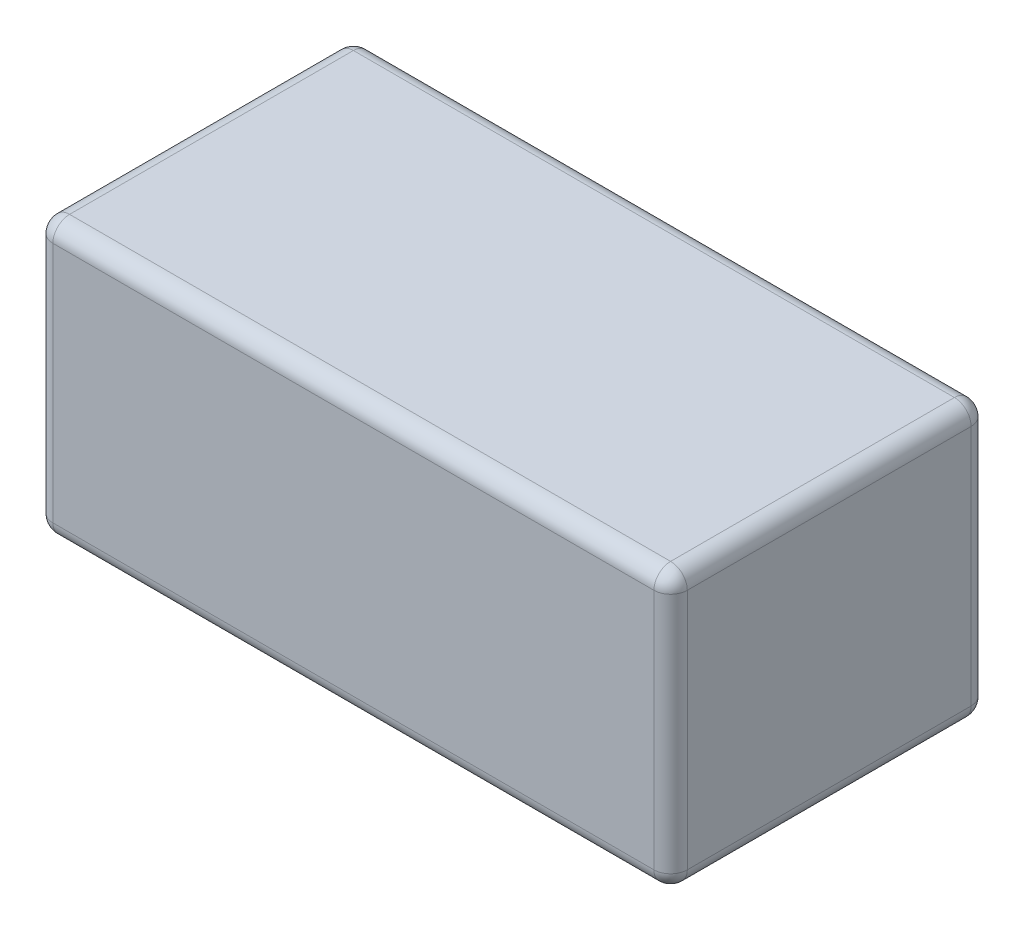
SolidWorks part; units mm, degrees
ref_plane "Front Plane" through (0, 0, 0) normal (0, 0, 1) x (1, 0, 0)
ref_plane "Top Plane" through (0, 0, 0) normal (0, 1, 0) x (1, 0, 0)
ref_plane "Right Plane" through (0, 0, 0) normal (1, 0, 0) x (0, 0, -1)
sketch "Sketch1" plane through (0, 0, 0) normal (0, 1, 0) x (1, 0, 0)
  line L1 (-38, -19) -> (38, -19)
  line L2 (-38, -19) -> (-38, 19)
  line L3 (-38, 19) -> (38, 19)
  line L4 (38, -19) -> (38, 19)
  line L5 (-38, -19) -> (38, 19) construction
  line L6 (-38, 19) -> (38, -19) construction
  point P0 (0, 0)
  dimension "D1" = 76
  dimension "D2" = 38
extrude "Boss-Extrude1" add sketch "Sketch1" along normal blind 33
fillet "Fillet1" radius 2 12 edges at (0, 33, 19) (-38, 33, 0) (-38, 16.5, 19) (-38, 0, 0) (0, 0, 19) (0, 33, -19) (-38, 16.5, -19) (0, 0, -19) (38, 16.5, 19) (38, 33, 0) (38, 16.5, -19) (38, 0, 0)
